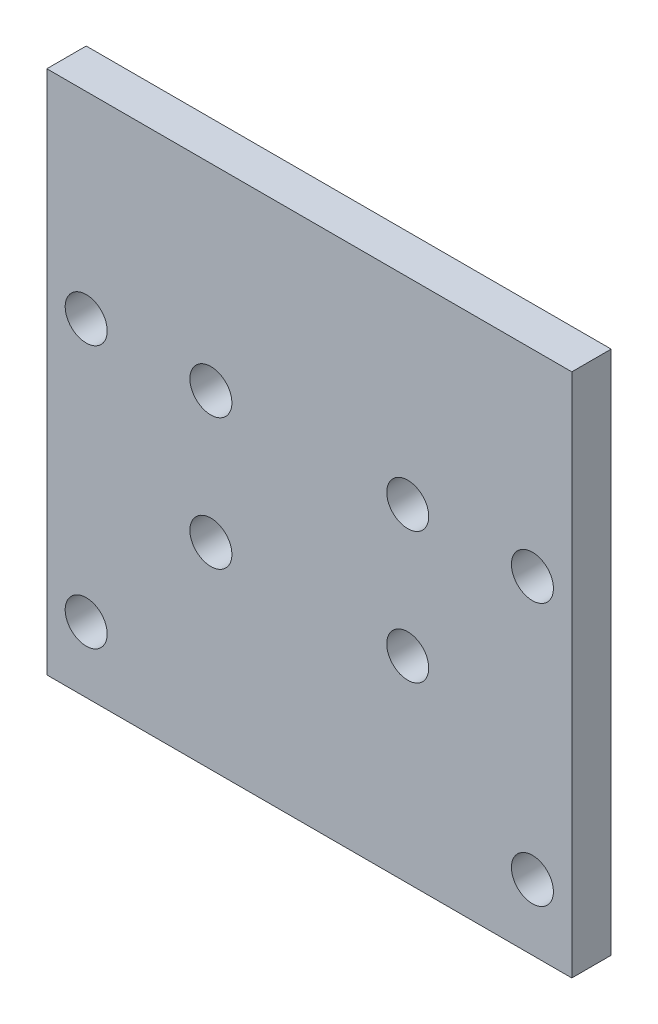
SolidWorks part; units mm, degrees
material "Thornel Mat VMA"
ref_plane "前视基准面" through (0, 0, 0) normal (0, 0, 1) x (1, 0, 0)
ref_plane "上视基准面" through (0, 0, 0) normal (0, 1, 0) x (1, 0, 0)
ref_plane "右视基准面" through (0, 0, 0) normal (1, 0, 0) x (0, 0, -1)
sketch "草图1" plane through (0, 0, 0) normal (0, 0, 1) x (1, 0, 0)
  line L1 (-20, -20) -> (20, -20)
  line L2 (-20, -20) -> (-20, 20)
  line L3 (-20, 20) -> (20, 20)
  line L4 (20, -20) -> (20, 20)
  line L5 (-20, -20) -> (20, 20) construction
  line L6 (-20, 20) -> (20, -20) construction
  point P0 (0, 0)
  dimension "D1" = 40
  dimension "D2" = 40
extrude "凸台-拉伸1" add sketch "草图1" along normal blind 3
sketch "草图2" plane through (0, 0, 3) normal (0, 0, 1) x (1, 0, 0)
  line L0 (0, -20) -> (0, -42.7603) construction
  line L1 (-7.5, -5) -> (7.5, -5) construction
  line L2 (-7.5, -5) -> (-7.5, 5) construction
  line L3 (-7.5, 5) -> (7.5, 5) construction
  line L4 (7.5, -5) -> (7.5, 5) construction
  line L5 (-7.5, -5) -> (7.5, 5) construction
  line L6 (-7.5, 5) -> (7.5, -5) construction
  line L7 (-20, -20) -> (20, -20) construction
  line L8 (-20, 20) -> (-20, -20) construction
  circle A0 centre (-7.5, 5) radius 1.6
  circle A1 centre (7.5, 5) radius 1.6
  circle A2 centre (7.5, -5) radius 1.6
  circle A3 centre (-7.5, -5) radius 1.6
  circle A4 centre (-17, -15) radius 1.6
  circle A5 centre (-17, 5) radius 1.6
  circle A6 centre (17, 5) radius 1.6
  circle A7 centre (17, -15) radius 1.6
  point P0 (0, 0)
  dimension "D3" = 3.2
  dimension "D4" = 3.2
  dimension "D6" = 5
  dimension "D7" = 3
  dimension "D8" = 20
  dimension "D1" = 15
  dimension "D2" = 10
  dimension "3" = 3
extrude "切除-拉伸1" cut sketch "草图2" against normal through all
